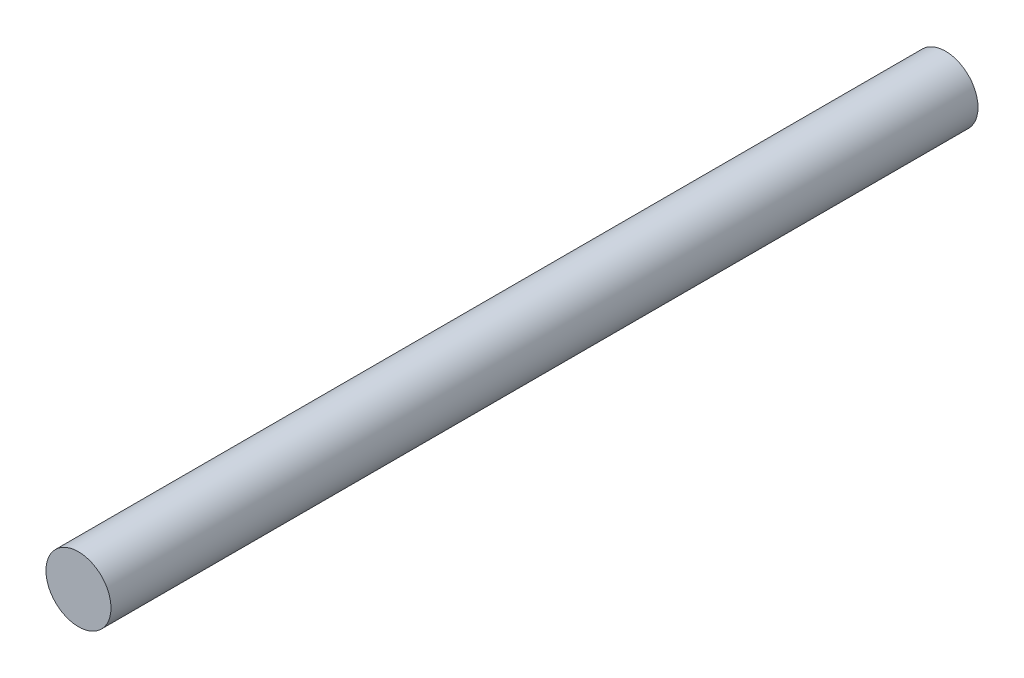
SolidWorks part; units mm, degrees
ref_plane "前视基准面" through (0, 0, 0) normal (0, 0, 1) x (1, 0, 0)
ref_plane "上视基准面" through (0, 0, 0) normal (0, 1, 0) x (1, 0, 0)
ref_plane "右视基准面" through (0, 0, 0) normal (1, 0, 0) x (0, 0, -1)
sketch "草图1" plane through (0, 0, 0) normal (0, 0, 1) x (1, 0, 0)
  circle A0 centre (0, 0) radius 1.5
  dimension "D1" = 3
extrude "凸台-拉伸1" add sketch "草图1" along normal blind 40
